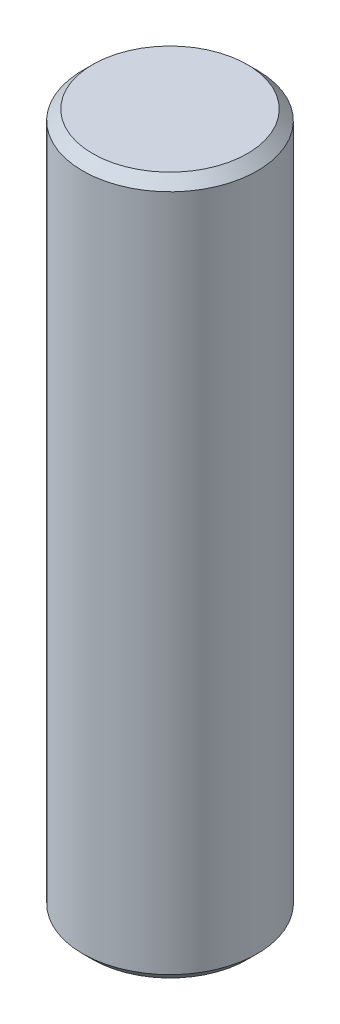
SolidWorks part; units mm, degrees
ref_plane "前视基准面" through (0, 0, 0) normal (0, 0, 1) x (1, 0, 0)
ref_plane "上视基准面" through (0, 0, 0) normal (0, 1, 0) x (1, 0, 0)
ref_plane "右视基准面" through (0, 0, 0) normal (1, 0, 0) x (0, 0, -1)
other "Configuration Table"
sketch "草图1" plane through (0, 0, 0) normal (0, 1, 0) x (1, 0, 0)
  circle A0 centre (0, 0) radius 1.75
  dimension "D1" = 3.5
extrude "凸台-拉伸1" add sketch "草图1" along normal blind 14
chamfer "倒角1" distance 0.2 angle 45 2 edges at (0, 0, 1.75) (0, 14, 1.75)
